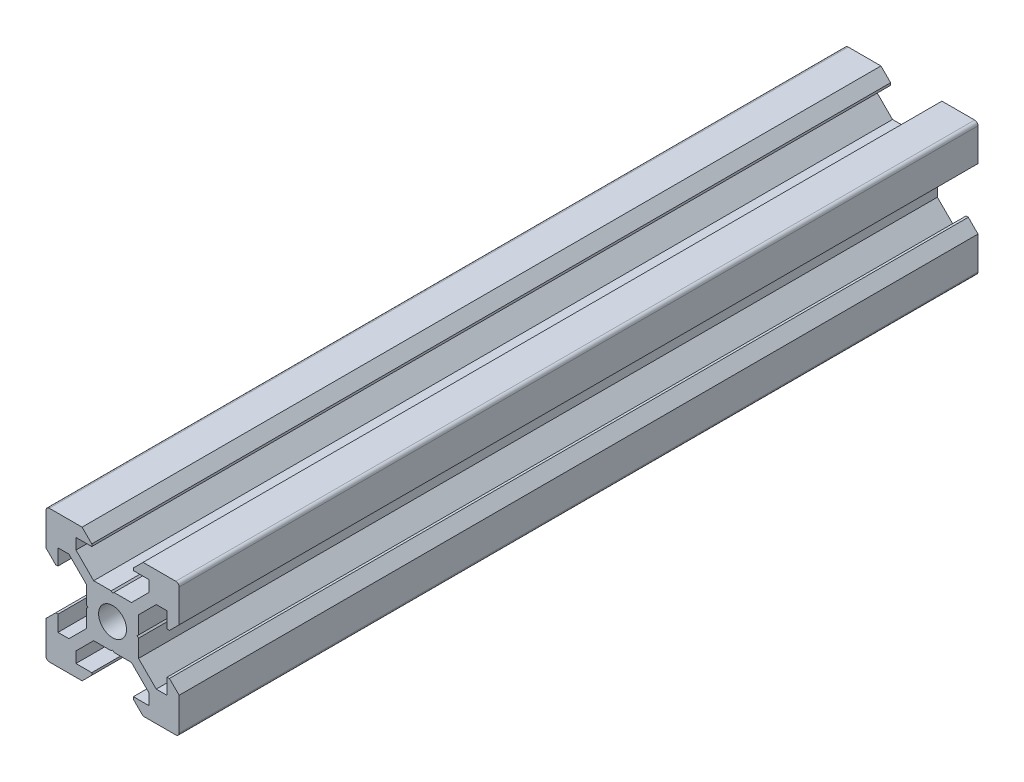
SolidWorks part; units mm, degrees
material "6061-T6 (SS)"
ref_plane "Front Plane" through (0, 0, 0) normal (0, 0, 1) x (1, 0, 0)
ref_plane "Top Plane" through (0, 0, 0) normal (0, 1, 0) x (1, 0, 0)
ref_plane "Right Plane" through (0, 0, 0) normal (1, 0, 0) x (0, 0, -1)
sketch "Sketch1" plane through (0, 0, 0) normal (0, 0, 1) x (1, 0, 0)
  line L1 (9.5, -10) -> (-9.5, -10)
  line L2 (10, -9.5) -> (10, 9.5)
  line L3 (9.5, 10) -> (-9.5, 10)
  line L4 (-10, -9.5) -> (-10, 9.5)
  line L5 (10, -10) -> (-10, 10) construction
  line L6 (10, 10) -> (-10, -10) construction
  circle A0 centre (0, 0) radius 2.1
  arc A1 (-9.5, 10) -> (-10, 9.5) centre (-9.5, 9.5) ccw
  arc A2 (10, 9.5) -> (9.5, 10) centre (9.5, 9.5) ccw
  arc A3 (9.5, -10) -> (10, -9.5) centre (9.5, -9.5) ccw
  arc A4 (-9.5, -10) -> (-10, -9.5) centre (-9.5, -9.5) cw
  point P0 (0, 0)
  line B0 (0, 0) -> (0, 10) construction
  line B1 (0, 3.69) -> (-0.21, 3.9)
  line B2 (-0.21, 3.9) -> (-2.8393, 3.9)
  line B3 (-2.8393, 3.9) -> (-5.5, 6.5607)
  line B4 (-5.5, 6.5607) -> (-5.5, 8.2)
  line B5 (-5.5, 8.2) -> (-3.125, 8.2)
  line B6 (-3.125, 8.2) -> (-3.125, 8.545)
  line B7 (-3.125, 8.545) -> (-4.58, 10)
  line B8 (-4.58, 10) -> (4.58, 10)
  line B9 (0, 0) -> (-5.9132, 5.9132) construction
  line B10 (3.125, 8.545) -> (4.58, 10)
  line B11 (3.125, 8.2) -> (3.125, 8.545)
  line B12 (5.5, 8.2) -> (3.125, 8.2)
  line B13 (5.5, 6.5607) -> (5.5, 8.2)
  line B14 (2.8393, 3.9) -> (5.5, 6.5607)
  line B15 (0.21, 3.9) -> (2.8393, 3.9)
  line B16 (0, 3.69) -> (0.21, 3.9)
  line B17 (0, 0) -> (-10, 0) construction
  line B18 (-3.69, 0) -> (-3.9, -0.21)
  line B19 (-3.9, -0.21) -> (-3.9, -2.8393)
  line B20 (-3.9, -2.8393) -> (-6.5607, -5.5)
  line B21 (-6.5607, -5.5) -> (-8.2, -5.5)
  line B22 (-8.2, -5.5) -> (-8.2, -3.125)
  line B23 (-8.2, -3.125) -> (-8.545, -3.125)
  line B24 (-8.545, -3.125) -> (-10, -4.58)
  line B25 (-10, -4.58) -> (-10, 4.58)
  line B26 (0, 0) -> (-5.9132, -5.9132) construction
  line B27 (-8.545, 3.125) -> (-10, 4.58)
  line B28 (-8.2, 3.125) -> (-8.545, 3.125)
  line B29 (-8.2, 5.5) -> (-8.2, 3.125)
  line B30 (-6.5607, 5.5) -> (-8.2, 5.5)
  line B31 (-3.9, 2.8393) -> (-6.5607, 5.5)
  line B32 (-3.9, 0.21) -> (-3.9, 2.8393)
  line B33 (-3.69, 0) -> (-3.9, 0.21)
  line B34 (0, 0) -> (0, -10) construction
  line B35 (0, -3.69) -> (0.21, -3.9)
  line B36 (0.21, -3.9) -> (2.8393, -3.9)
  line B37 (2.8393, -3.9) -> (5.5, -6.5607)
  line B38 (5.5, -6.5607) -> (5.5, -8.2)
  line B39 (5.5, -8.2) -> (3.125, -8.2)
  line B40 (3.125, -8.2) -> (3.125, -8.545)
  line B41 (3.125, -8.545) -> (4.58, -10)
  line B42 (4.58, -10) -> (-4.58, -10)
  line B43 (0, 0) -> (5.9132, -5.9132) construction
  line B44 (-3.125, -8.545) -> (-4.58, -10)
  line B45 (-3.125, -8.2) -> (-3.125, -8.545)
  line B46 (-5.5, -8.2) -> (-3.125, -8.2)
  line B47 (-5.5, -6.5607) -> (-5.5, -8.2)
  line B48 (-2.8393, -3.9) -> (-5.5, -6.5607)
  line B49 (-0.21, -3.9) -> (-2.8393, -3.9)
  line B50 (0, -3.69) -> (-0.21, -3.9)
  line B51 (0, 0) -> (10, 0) construction
  line B52 (3.69, 0) -> (3.9, 0.21)
  line B53 (3.9, 0.21) -> (3.9, 2.8393)
  line B54 (3.9, 2.8393) -> (6.5607, 5.5)
  line B55 (6.5607, 5.5) -> (8.2, 5.5)
  line B56 (8.2, 5.5) -> (8.2, 3.125)
  line B57 (8.2, 3.125) -> (8.545, 3.125)
  line B58 (8.545, 3.125) -> (10, 4.58)
  line B59 (10, 4.58) -> (10, -4.58)
  line B60 (0, 0) -> (5.9132, 5.9132) construction
  line B61 (8.545, -3.125) -> (10, -4.58)
  line B62 (8.2, -3.125) -> (8.545, -3.125)
  line B63 (8.2, -5.5) -> (8.2, -3.125)
  line B64 (6.5607, -5.5) -> (8.2, -5.5)
  line B65 (3.9, -2.8393) -> (6.5607, -5.5)
  line B66 (3.9, -0.21) -> (3.9, -2.8393)
  line B67 (3.69, 0) -> (3.9, -0.21)
  dimension "D1" = 4.2
  dimension "D3" = 0.5
  dimension "D2" = 20
sketch_block_instance "V Slot 1-4"
sketch_block "V Slot 1" parameters "D1"=10, "D2"=11, "D3"=4.3, "D4"=1.8, "D5"=0.21, "D6"=45, "D7"=9.16, "D8"=1.5, "D9"=6.25
sketch_block_instance "V Slot 1-5"
sketch_block_instance "V Slot 1-6"
sketch_block_instance "V Slot 1-7"
extrude "Boss-Extrude1" add sketch "Sketch1" along normal blind 120 contours B67 B52 B53 B54 B55 B56 B57 B58 L2 A2 L3 B10 B11 B12 B13 B14 B15 B16 B1 B2 B3 B4 B5 B6 B7 A1 L4 B27 B28 B29 B30 B31 B32 B33 B18 B19 B20 B21 B22 B23 B24 A4 L1 B44 B45 B46 B47 B48 B49
